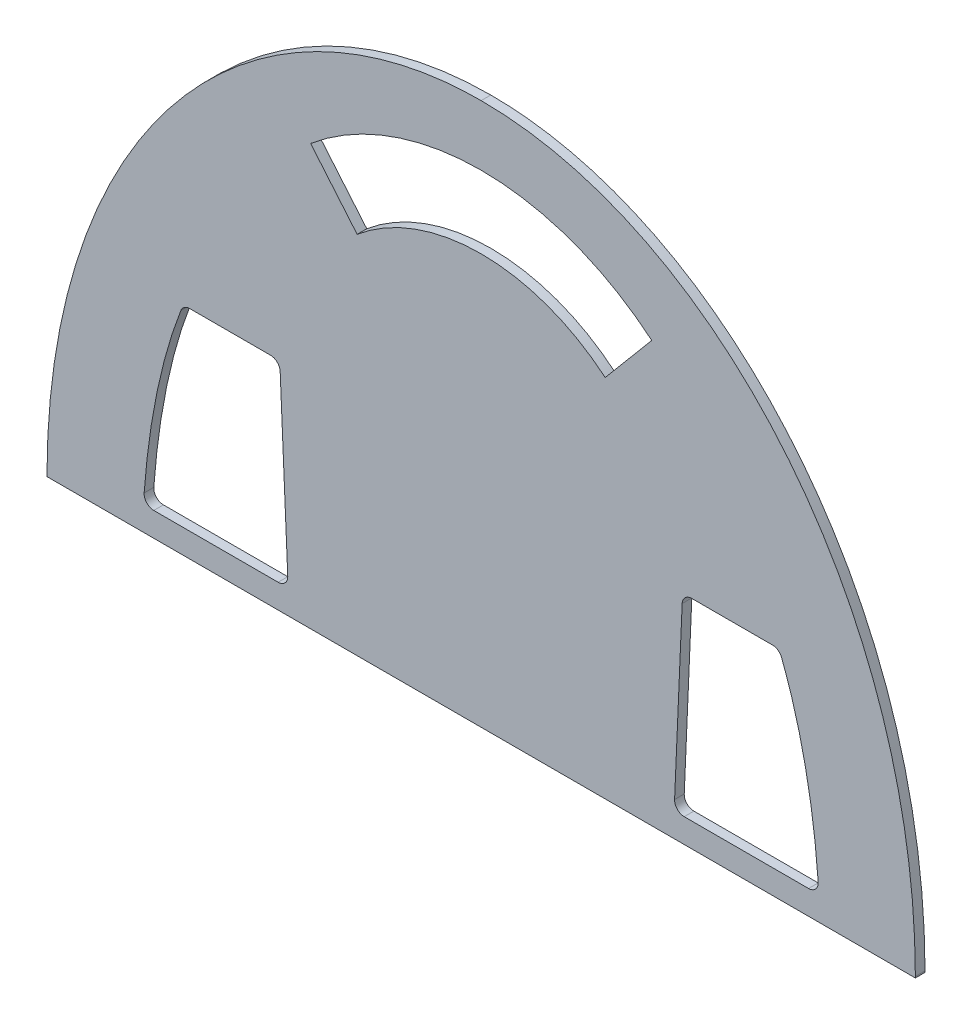
SolidWorks part; units mm, degrees
ref_plane "Front Plane" through (0, 0, 0) normal (0, 0, 1) x (1, 0, 0)
ref_plane "Top Plane" through (0, 0, 0) normal (0, 1, 0) x (1, 0, 0)
ref_plane "Right Plane" through (0, 0, 0) normal (1, 0, 0) x (0, 0, -1)
sketch "Sketch2" plane through (0, 0, 0) normal (0, 0, 1) x (1, 0, 0)
  line L0 (-90, 0) -> (90, 0)
  line L3 (90, 0.2751) -> (90, 0) construction
  line L4 (90, 0.2751) -> (90, 0)
  line L5 (-90, 0) -> (-90, 0.2751) construction
  line L6 (-90, 0) -> (-90, 0.2751)
  spline S0 degree 3 poles (14.3448, -887.3955) (563.4425, 966.1536) (-999.1415, -307.2489) (826.1831, -400.4764) knots -2.216235 -2.216235 -2.216235 -2.216235 3.127585 3.127585 3.127585 3.127585 only from (0, 112.5003) to (-90, 0.2751) construction
  spline S1 degree 3 poles (0, 112.5003) (-47.92, 112.5003) (-89.8827, 65.7231) (-90, 0.2751) knots 0.001399 0.001399 0.001399 0.001399 1 1 1 1
  spline S2 degree 3 poles (-826.184, -400.4765) (999.1422, -307.2493) (-563.4429, 966.1542) (-14.3446, -887.3961) knots -2.126187 -2.126187 -2.126187 -2.126187 3.217634 3.217634 3.217634 3.217634 only from (90, 0.2751) to (0, 112.5003) construction
  spline S3 degree 3 poles (90, 0.2751) (89.8827, 65.7231) (47.92, 112.5003) (0, 112.5003) knots 0.001399 0.001399 0.001399 0.001399 1 1 1 1
  point P6 (0, 5.1729)
  point P7 (0, 5.5096)
  point P12 (2.8442, 0)
  point P13 (78.554, 0)
  point P16 (0, 63.22)
  point P19 (90, 0)
  point P21 (0, 94.7375)
extrude "Boss-Extrude1" add sketch "Sketch2" along normal blind 2
sketch "Sketch3" plane through (0, 0, 2) normal (0, 0, 1) x (1, 0, 0)
  line L0 (-70, 5) -> (-40, 5)
  line L1 (-40, 5) -> (-41.7448, 44.9619)
  line L2 (-41.7448, 44.9619) -> (-61.7448, 44.9619)
  line L3 (-90, 0) -> (90, 0) construction
  line L4 (0, 0) -> (0, 233.7715) construction
  line L5 (40, 5) -> (41.7448, 44.9619)
  line L6 (41.7448, 44.9619) -> (61.7448, 44.9619)
  line L7 (70, 5) -> (40, 5)
  line L8 (-35.3533, 87.1324) -> (-25.7115, 75.6418)
  line L9 (35.3533, 87.1324) -> (25.7115, 75.6418)
  arc A0 (-35.3533, 87.1324) -> (35.3533, 87.1324) centre (0, 45) cw
  arc A1 (25.7115, 75.6418) -> (-25.7115, 75.6418) centre (0, 45) ccw
  ellipse E0 centre (-39.5634, -5) end of major axis (-39.5634, 67.1828) minor radius 30.733 (-70, 5) -> (-61.7448, 44.9619) cw
  ellipse E2 centre (39.5634, -5) end of major axis (39.5634, 67.1828) minor radius 30.733 (70, 5) -> (61.7448, 44.9619) ccw
  point P26 (-14.1377, 88.6819)
  point P29 (0, 233.7715)
  point P36 (21.5889, 93.5426)
  point P37 (0, 0)
  point P38 (-21.8856, 92.3535)
  point P39 (22.7368, 84.3186)
  point P40 (0, 26.496)
  point P41 (0, 33.2619)
  point P42 (18.4116, 67.1828)
  point P43 (32.0211, 94.3627)
  point P44 (18.4209, 65.5059)
  point P45 (17.8293, 65.8067)
  point P46 (-24.4753, 83.6577)
  point P47 (17.1704, 83.6306)
  point P48 (21.1057, 96.4202)
  point P49 (21.8436, 80.6791)
  point P50 (32.4196, 90.5173)
  point P51 (25.5076, 80.8117)
  dimension "D9" = 40
  dimension "D10" = 55
  dimension "D1" = 30
  dimension "D2" = 40
  dimension "D3" = 20
  dimension "D4" = 5
  dimension "D5" = 40
  dimension "D6" = 5
  dimension "D7" = 87.5
  dimension "D8" = 45
  dimension "D11" = 80
extrude "Cut-Extrude1" cut sketch "Sketch3" against normal through all
fillet "Fillet1" radius 2 8 edges at (70, 5, 1) (61.7448, 44.9619, 1) (41.7448, 44.9619, 1) (40, 5, 1) (-61.7448, 44.9619, 1) (-41.7448, 44.9619, 1) (-40, 5, 1) (-70, 5, 1)
